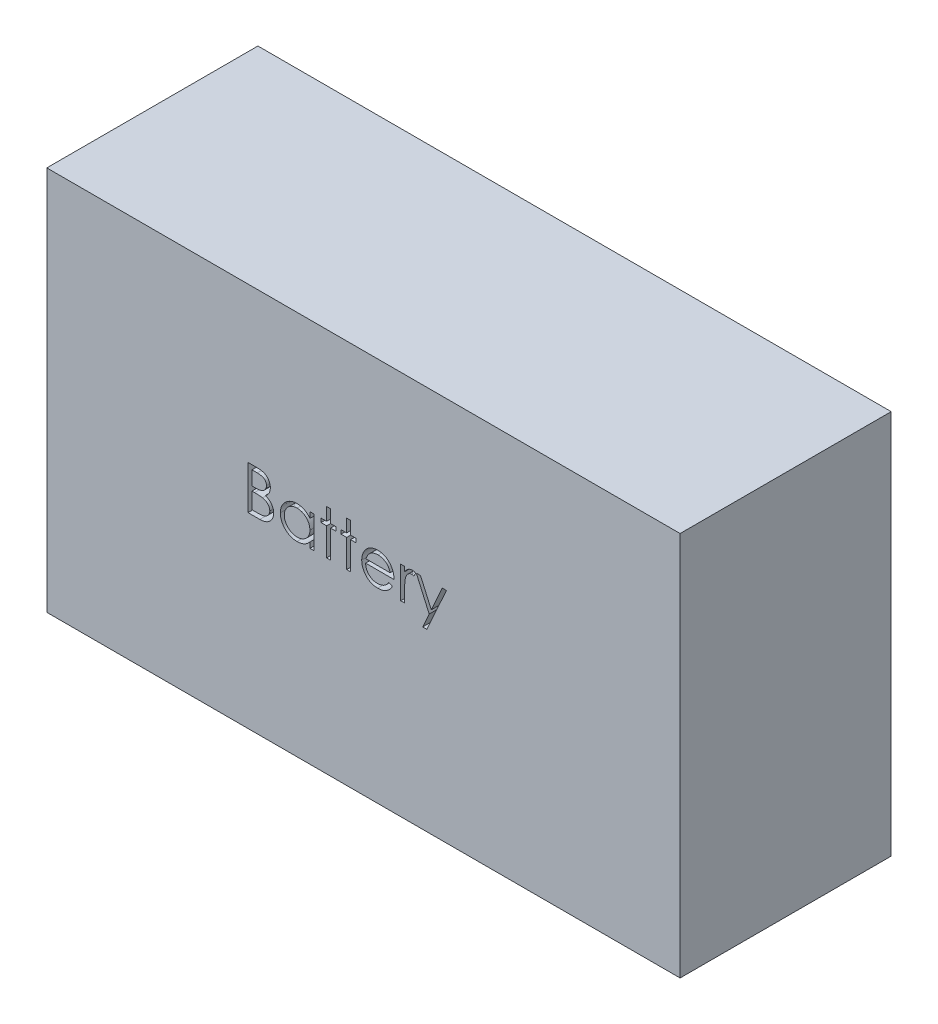
SolidWorks part; units mm, degrees
ref_plane "Front Plane" through (0, 0, 0) normal (0, 0, 1) x (1, 0, 0)
ref_plane "Top Plane" through (0, 0, 0) normal (0, 1, 0) x (1, 0, 0)
ref_plane "Right Plane" through (0, 0, 0) normal (1, 0, 0) x (0, 0, -1)
sketch "Sketch1" plane through (0, 0, 0) normal (0, 0, 1) x (1, 0, 0)
  line L1 (-25.5, -15.5) -> (25.5, -15.5)
  line L2 (-25.5, -15.5) -> (-25.5, 15.5)
  line L3 (-25.5, 15.5) -> (25.5, 15.5)
  line L4 (25.5, -15.5) -> (25.5, 15.5)
  line L5 (-25.5, -15.5) -> (25.5, 15.5) construction
  line L6 (-25.5, 15.5) -> (25.5, -15.5) construction
  point P0 (0, 0)
  dimension "D1" = 51
  dimension "D2" = 31
extrude "Boss-Extrude1" add sketch "Sketch1" along normal blind 17
sketch "Sketch2" plane through (0, 0, 17) normal (0, 0, 1) x (1, 0, 0)
  text T0 "Battery"
extrude "Cut-Extrude1" cut sketch "Sketch2" against normal blind 2
